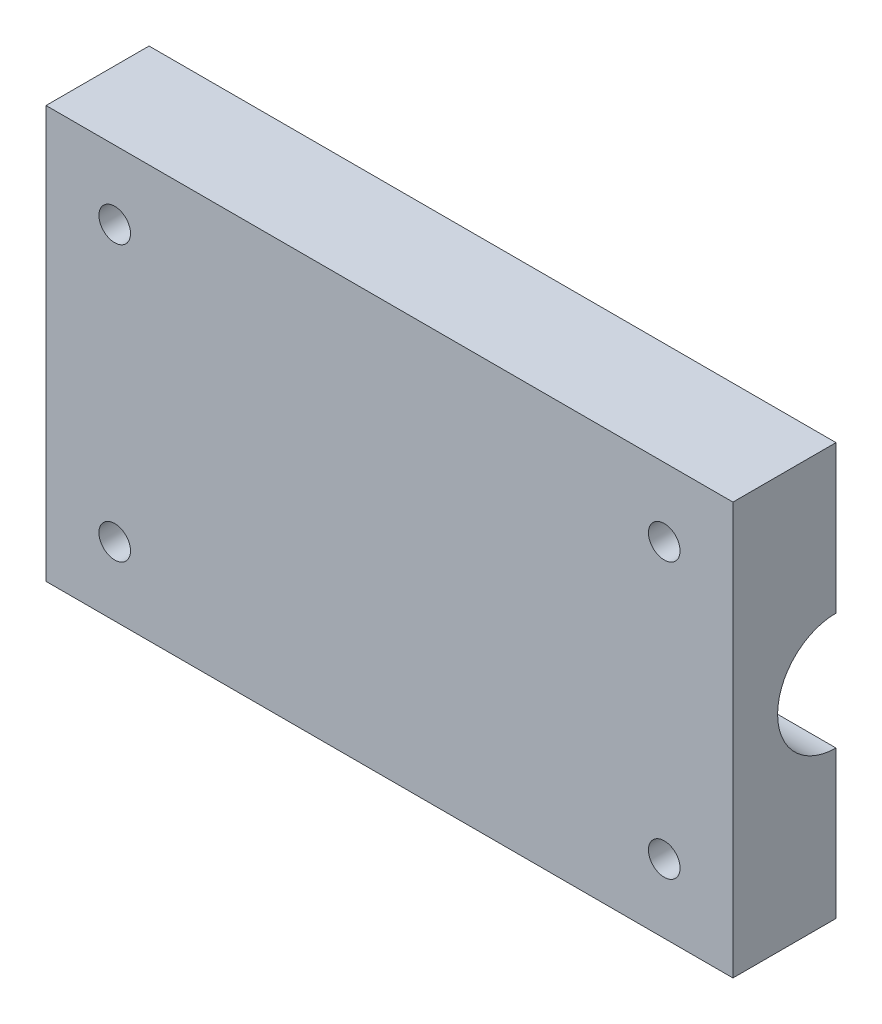
SolidWorks part; units mm, degrees
ref_plane "Front Plane" through (0, 0, 0) normal (0, 0, 1) x (1, 0, 0)
ref_plane "Top Plane" through (0, 0, 0) normal (0, 1, 0) x (1, 0, 0)
ref_plane "Right Plane" through (0, 0, 0) normal (1, 0, 0) x (0, 0, -1)
sketch "Sketch1" plane through (0, 0, 0) normal (0, 0, 1) x (1, 0, 0)
  line L0 (0, -55) -> (0, 55) construction
  line L1 (-50, 30) -> (50, 30)
  line L2 (-50, 30) -> (-50, -30)
  line L3 (-50, -30) -> (50, -30)
  line L4 (50, 30) -> (50, -30)
  line L5 (-50, 30) -> (50, -30) construction
  line L6 (-50, -30) -> (50, 30) construction
  line L7 (55, 0) -> (-55, 0) construction
  circle A0 centre (-40, -20) radius 2.3
  circle A1 centre (40, -20) radius 2.3
  circle A2 centre (40, 20) radius 2.3
  circle A3 centre (-40, 20) radius 2.3
  point P0 (0, 0)
  dimension "D3" = 4.6
  dimension "D1" = 60
  dimension "D2" = 100
  dimension "D4" = 10
  dimension "D5" = 10
extrude "Boss-Extrude1" add sketch "Sketch1" along normal blind 15
sketch "Sketch2" plane through (-50, 0, 0) normal (-1, 0, 0) x (0, 0, 1)
  circle A0 centre (0, 0) radius 8.5
  dimension "D1" = 17
extrude "Cut-Extrude1" cut sketch "Sketch2" against normal mid plane 400
